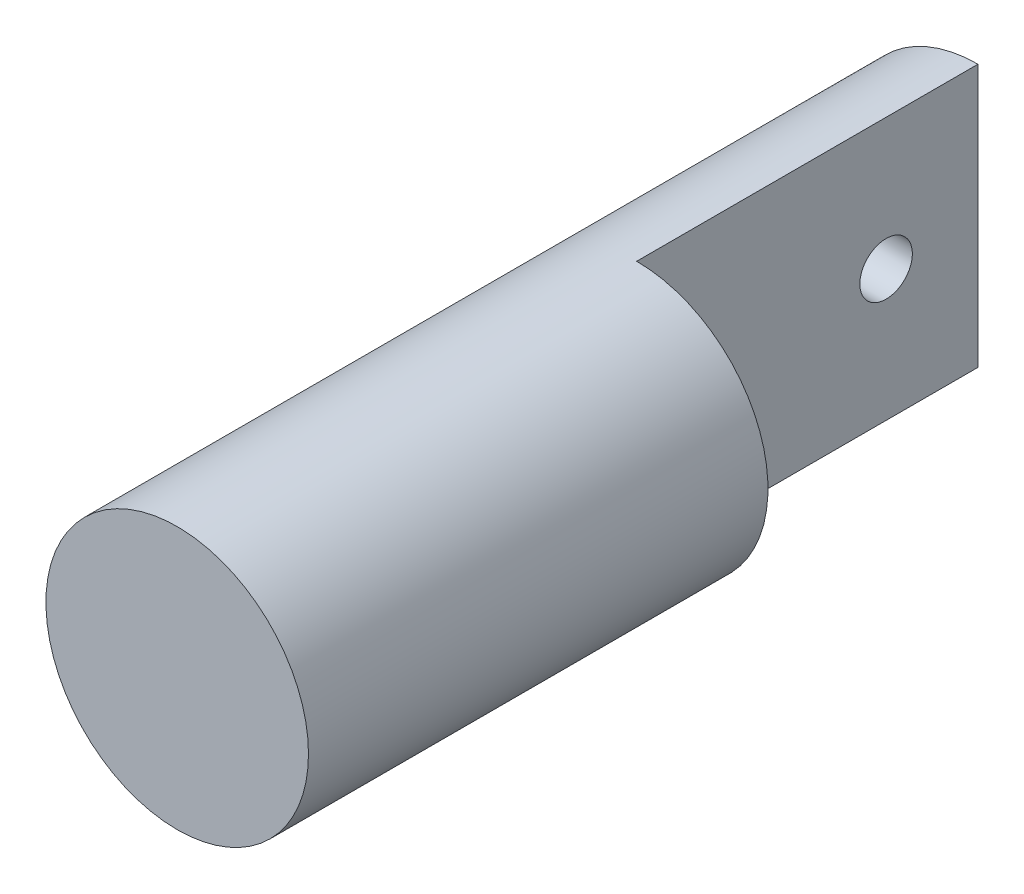
SolidWorks part; units mm, degrees
material "2024-T3"
ref_plane "正面" through (0, 0, 0) normal (0, 0, 1) x (1, 0, 0)
ref_plane "平面" through (0, 0, 0) normal (0, 1, 0) x (1, 0, 0)
ref_plane "右側面" through (0, 0, 0) normal (1, 0, 0) x (0, 0, -1)
sketch "ｽｹｯﾁ1" plane through (0, 0, 0) normal (0, 0, 1) x (1, 0, 0)
  circle A0 centre (0, 0) radius 10
  dimension "D1" = 20
extrude "ﾎﾞｽ - 押し出し1" add sketch "ｽｹｯﾁ1" along normal blind 27
sketch "ｽｹｯﾁ3" plane through (0, 0, 0) normal (0, 0, -1) x (-1, 0, 0)
  line L1 (-10, 10) -> (0, 10)
  line L2 (-10, 10) -> (-10, -10)
  line L3 (-10, -10) -> (0, -10)
  line L4 (0, 10) -> (0, -10)
  line L5 (-10, 10) -> (0, -10) construction
  line L6 (-10, -10) -> (0, 10) construction
  circle A0 centre (0, 0) radius 10 construction
  point P0 (-5, 0)
  dimension "D1" = 0
extrude "ｶｯﾄ - 押し出し2" cut sketch "ｽｹｯﾁ3" against normal blind 26
sketch "ｽｹｯﾁ4" plane through (0, 0, 0) normal (1, 0, 0) x (0, 0, -1)
  line L0 (0, 10) -> (0, -10) construction
  line L1 (-26, 10) -> (0, 10) construction
  circle A0 centre (-7, 0) radius 2
  dimension "D1" = 4
  dimension "D2" = 7
  dimension "D3" = 10
sketch "ｽｹｯﾁ5" plane through (0, 0, 27) normal (0, 0, 1) x (1, 0, 0)
  circle A0 centre (0, 0) radius 10
extrude "ﾎﾞｽ - 押し出し2" add sketch "ｽｹｯﾁ5" along normal blind 34
extrude "ｶｯﾄ - 押し出し3" cut sketch "ｽｹｯﾁ4" against normal through all
sketch "ｽｹｯﾁ6" plane through (0, 0, 0) normal (0, 0, -1) x (-1, 0, 0)
  line L0 (0, 10) -> (0, -10) construction
  point P0 (5, 0)
  dimension "D1" = 5
  dimension "D2" = 10
hole_wizard "M3x0.5 ねじ穴1" positions "ｽｹｯﾁ6" profile "ｽｹｯﾁ7" tap size "M3x0.5" standard "JIS"
sketch "ｽｹｯﾁ7" plane through (-5, 0, 0) normal (1, 0, 0) x (0, 1, 0)
  line L0 (0, 0) -> (0, 5)
  line L1 (0, 5) -> (1.25, 5)
  line L2 (1.25, 5) -> (1.25, 0)
  line L5 (1.25, 0) -> (0, 0)
  line L11 (0, -6.35) -> (0, 107.95) construction
  dimension "次ｻｰﾌｪｽまでのねじ下穴ﾄﾞﾘﾙ直径" = 2.5
  dimension "次ｻｰﾌｪｽまでのねじ下穴ﾄﾞﾘﾙの深さ" = 5
cosmetic thread "穴のねじ山1" parameters "D2"=3
